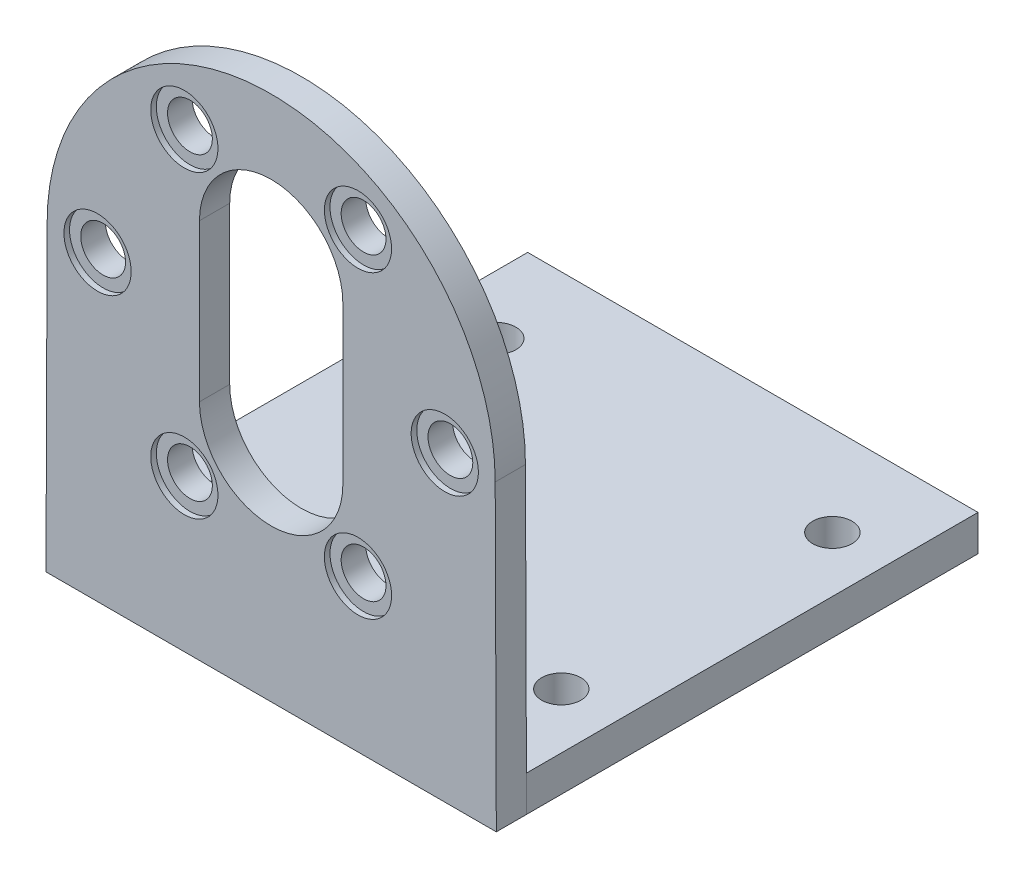
SolidWorks part; units mm, degrees
ref_plane "前视基准面" through (0, 0, 0) normal (0, 0, 1) x (1, 0, 0)
ref_plane "上视基准面" through (0, 0, 0) normal (0, 1, 0) x (1, 0, 0)
ref_plane "右视基准面" through (0, 0, 0) normal (1, 0, 0) x (0, 0, -1)
sketch "草图1" plane through (0, 0, 0) normal (0, 1, 0) x (1, 0, 0)
  line L1 (-20.1, 21.5) -> (20.1, 21.5)
  line L2 (-20.1, 21.5) -> (-20.1, -21.5)
  line L3 (-20.1, -21.5) -> (20.1, -21.5)
  line L4 (20.1, 21.5) -> (20.1, -21.5)
  point P4 (0, 0)
extrude "凸台-拉伸1" add sketch "草图1" along normal blind 3.2
sketch "草图3" plane through (0, 3.2, 0) normal (0, 1, 0) x (1, 0, 0)
  line L0 (20.1, -21.5) -> (20.1, 21.5) construction
  line L1 (-20.1, -21.5) -> (20.1, -21.5)
  line L2 (-20.1, -21.5) -> (-20.1, -18.8)
  line L3 (-20.1, -18.8) -> (20.1, -18.8)
  line L4 (20.1, -21.5) -> (20.1, -18.8)
  dimension "D1" = 2.7
extrude "凸台-拉伸3" add sketch "草图3" along normal blind 43.8
sketch "草图4" plane through (0, 0, 21.5) normal (0, 0, 1) x (1, 0, 0)
  line L0 (-20, 27) -> (-20.1, 0)
  line L1 (-20.1, 0) -> (20.1, 0)
  line L2 (20.1, 0) -> (20, 27)
  arc A0 (20, 27) -> (-20, 27) centre (0, 27) ccw
extrude "切除-拉伸2" cut sketch "草图4" against normal blind 2.7 flip side to cut
sketch "草图5" plane through (0, 3.2, 0) normal (0, 1, 0) x (1, 0, 0)
  line L0 (20.1, 21.5) -> (-20.1, 21.5) construction
  line L1 (-20.1, 21.5) -> (-20.1, -18.8) construction
  circle A0 centre (-14.85, 13.45) radius 1.75
  circle A1 centre (15.15, -10.75) radius 1.75
  circle A2 centre (-14.85, -10.75) radius 1.75
  circle A3 centre (15.15, 13.45) radius 1.75
  dimension "D1" = 8.05
  dimension "D5" = 3.5
  dimension "D2" = 5.25
  dimension "D3" = 30
  dimension "D4" = 24.2
extrude "切除-拉伸3" cut sketch "草图5" against normal through all
sketch "草图6" plane through (0, 0, 21.5) normal (0, 0, 1) x (1, 0, 0)
  line L0 (-6.4, 34) -> (-6.4, 20)
  line L1 (6.4, 34) -> (6.4, 20)
  arc A0 (6.4, 34) -> (-6.4, 34) centre (0, 34) ccw
  arc A1 (-6.4, 20) -> (6.4, 20) centre (0, 20) ccw
extrude "切除-拉伸4" cut sketch "草图6" against normal blind 3.2
sketch "草图7" plane through (0, 0, 21.5) normal (0, 0, 1) x (1, 0, 0)
  circle A2 centre (-7.75, 40.4) radius 2
  circle A3 centre (7.75, 40.4) radius 2
  circle A4 centre (-15.5, 27) radius 2
  circle A5 centre (15.5, 27) radius 2
  circle A6 centre (-7.75, 13.6) radius 2
  circle A7 centre (7.75, 13.6) radius 2
extrude "切除-拉伸5" cut sketch "草图7" against normal blind 3.2
sketch "草图8" plane through (0, 0, 21.5) normal (0, 0, 1) x (1, 0, 0)
  circle A0 centre (-7.75, 40.4) radius 3
  circle A1 centre (7.75, 40.4) radius 3
  circle A2 centre (-15.5, 27) radius 3
  circle A3 centre (15.5, 27) radius 3
  circle A4 centre (-7.75, 13.6) radius 3
  circle A5 centre (7.75, 13.6) radius 3
extrude "切除-拉伸6" cut sketch "草图8" against normal blind 0.5
